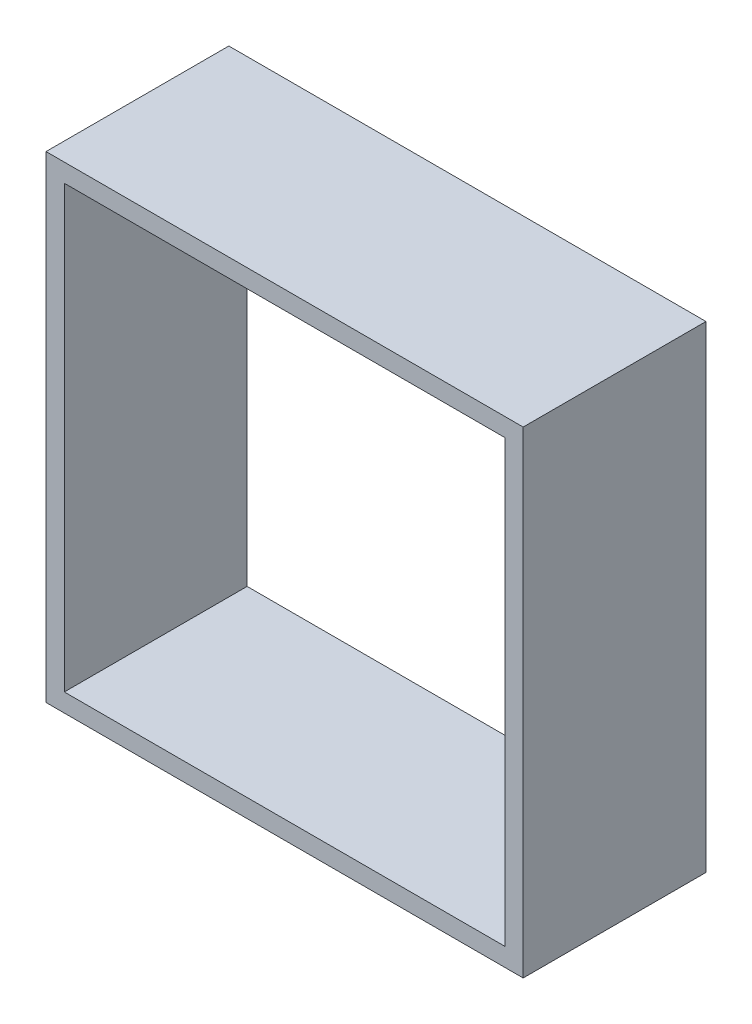
SolidWorks part; units mm, degrees
ref_plane "Front Plane" through (0, 0, 0) normal (0, 0, 1) x (1, 0, 0)
ref_plane "Top Plane" through (0, 0, 0) normal (0, 1, 0) x (1, 0, 0)
ref_plane "Right Plane" through (0, 0, 0) normal (1, 0, 0) x (0, 0, -1)
sketch "Sketch1" plane through (0, 0, 0) normal (0, 0, 1) x (1, 0, 0)
  line L0 (6.025, -6.025) -> (-6.025, 6.025) construction
  line L1 (-6.025, -6.025) -> (6.025, -6.025)
  line L2 (-6.025, -6.025) -> (-6.025, 6.025)
  line L3 (-6.025, 6.025) -> (6.025, 6.025)
  line L4 (6.025, -6.025) -> (6.025, 6.025)
  line L12 (-6.525, -6.525) -> (-6.525, 6.525)
  line L21 (-6.525, 6.525) -> (6.525, 6.525)
  line L22 (6.525, -6.525) -> (6.525, 6.525)
  line L23 (-6.525, -6.525) -> (6.525, -6.525)
  point P4 (0, 0)
  point P5 (0, 0)
  point P6 (0, 0)
  dimension "D1" = 12.05
  dimension "D2" = 12.05
  dimension "D3" = 0.5
extrude "Boss-Extrude1" add sketch "Sketch1" along normal blind 5
